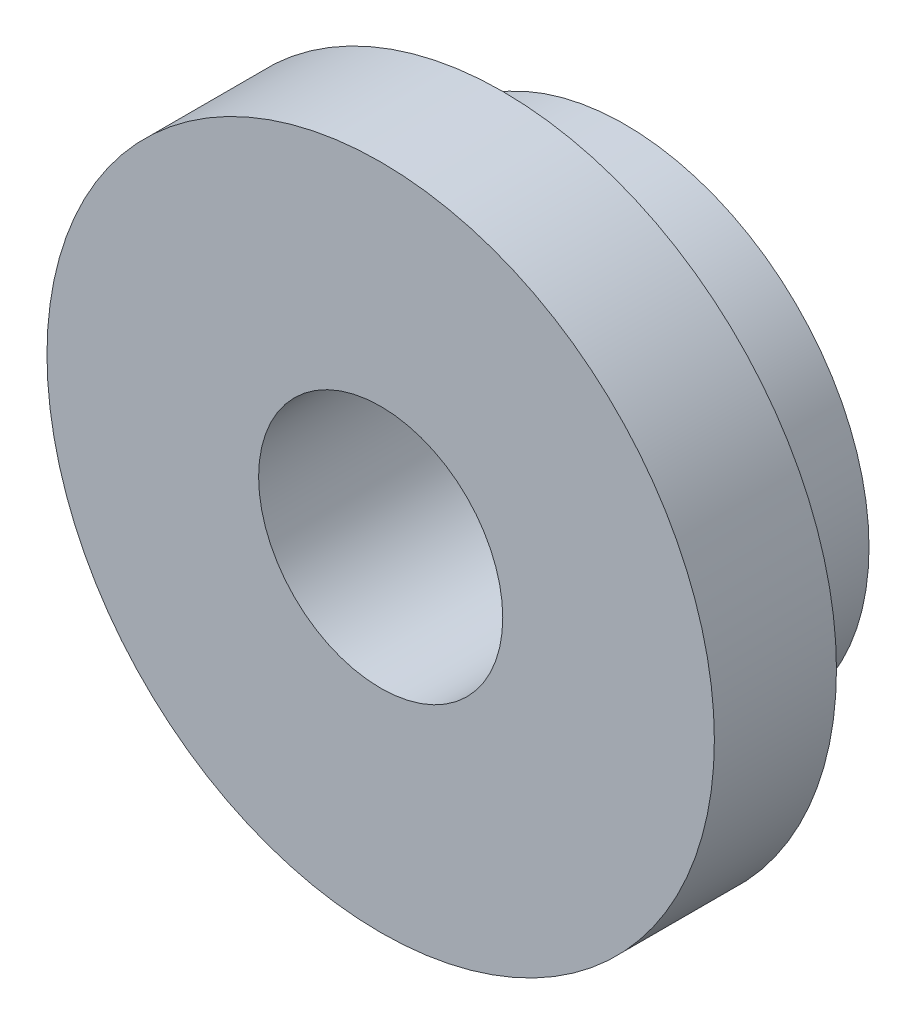
SolidWorks part; units mm, degrees
ref_plane "Front Plane" through (0, 0, 0) normal (0, 0, 1) x (1, 0, 0)
ref_plane "Top Plane" through (0, 0, 0) normal (0, 1, 0) x (1, 0, 0)
ref_plane "Right Plane" through (0, 0, 0) normal (1, 0, 0) x (0, 0, -1)
sketch "Sketch1" plane through (0, 0, 0) normal (0, 0, 1) x (1, 0, 0)
  circle A0 centre (0, 0) radius 6.35
  circle A1 centre (0, 0) radius 3.175
extrude "Boss-Extrude1" add sketch "Sketch1" along normal blind 3.175
sketch "Sketch2" plane through (0, 0, 3.175) normal (0, 0, 1) x (1, 0, 0)
  circle A0 centre (0, 0) radius 3.175
  circle A1 centre (0, 0) radius 8.6783
extrude "Boss-Extrude2" add sketch "Sketch2" along normal blind 3.175
